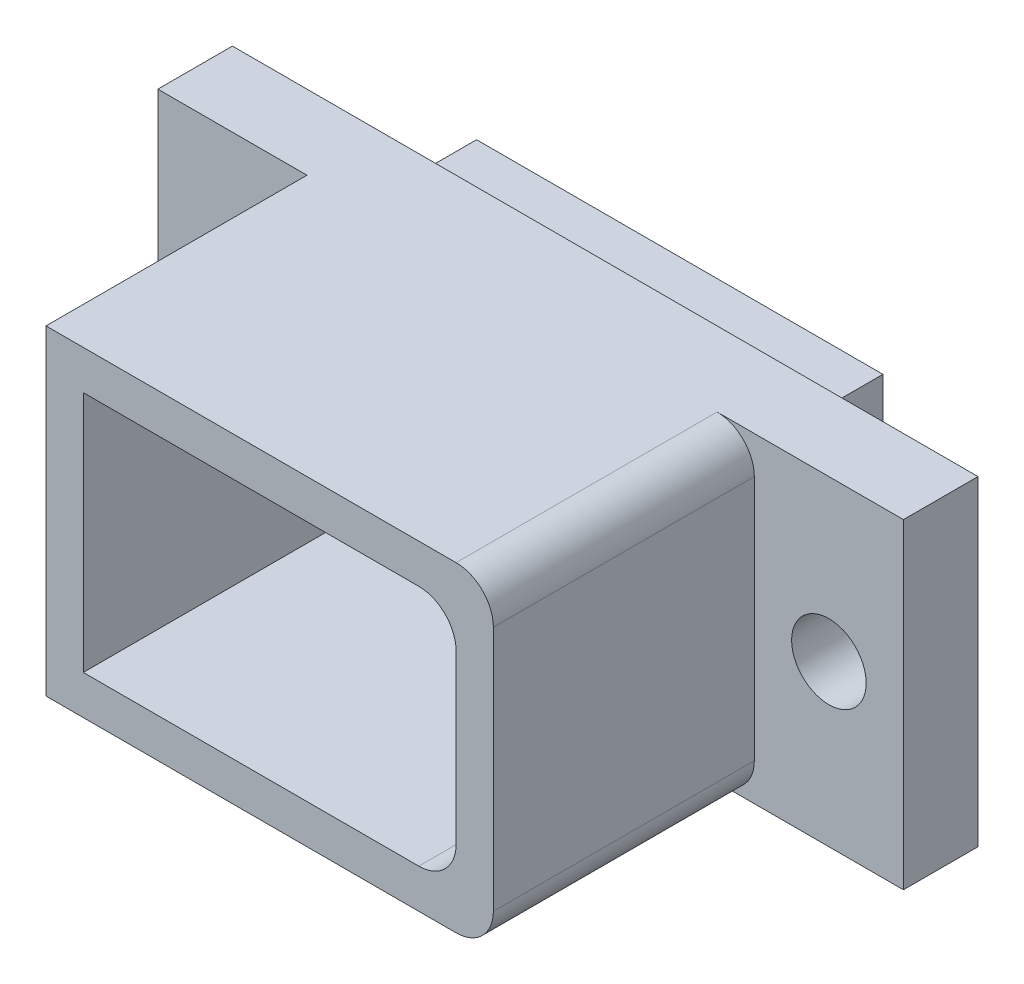
SolidWorks part; units mm, degrees
ref_plane "前视基准面" through (0, 0, 0) normal (0, 0, 1) x (1, 0, 0)
ref_plane "上视基准面" through (0, 0, 0) normal (0, 1, 0) x (1, 0, 0)
ref_plane "右视基准面" through (0, 0, 0) normal (1, 0, 0) x (0, 0, -1)
other "Configuration Table"
sketch "草图1" plane through (0, 0, 0) normal (0, 0, 1) x (1, 0, 0)
  line L0 (-3, 1.5) -> (0, 1.5) construction
  line L1 (-5.45, 3.4) -> (5.45, 3.4)
  line L2 (-5.45, 3.4) -> (-5.45, -3.4)
  line L3 (-5.45, -3.4) -> (5.45, -3.4)
  line L4 (5.45, 3.4) -> (5.45, -3.4)
  line L5 (-5.45, 3.4) -> (5.45, -3.4) construction
  line L6 (-5.45, -3.4) -> (5.45, 3.4) construction
  line L7 (-3, 1.5) -> (-3, -1.5) construction
  circle A0 centre (-3, 1.5) radius 0.5
  circle A1 centre (0, 1.5) radius 0.5
  circle A2 centre (3, 1.5) radius 0.5
  circle A3 centre (0, -1.5) radius 0.5
  circle A4 centre (3, -1.5) radius 0.5
  circle A5 centre (-3, -1.5) radius 0.5
  point P0 (0, 0)
  dimension "D10" = 1
  dimension "D1" = 6.8
  dimension "D2" = 10.9
  dimension "D3" = 2.45
  dimension "D4" = 1.9
  dimension "D5" = 90
  dimension "D6" = 3
  dimension "D7" = 3
  dimension "D8" = 3
  dimension "D9" = 2
extrude "凸台-拉伸1" add sketch "草图1" along normal blind 2
sketch "草图2" plane through (0, 0, 2) normal (0, 0, 1) x (1, 0, 0)
  line L0 (0, 0) -> (0, 9.4952) construction
  line L1 (-10, 4.3) -> (10, 4.3)
  line L2 (-10, 4.3) -> (-10, -4.3)
  line L3 (-10, -4.3) -> (10, -4.3)
  line L4 (10, 4.3) -> (10, -4.3)
  line L5 (-10, 4.3) -> (10, -4.3) construction
  line L6 (-10, -4.3) -> (10, 4.3) construction
  circle A0 centre (-8, 0) radius 1
  circle A1 centre (8, 0) radius 1
  circle A2 centre (3, 1.5) radius 0.5 construction
  circle A3 centre (3, -1.5) radius 0.5 construction
  circle A4 centre (0, -1.5) radius 0.5 construction
  circle A5 centre (0, 1.5) radius 0.5 construction
  circle A6 centre (-3, -1.5) radius 0.5 construction
  circle A7 centre (-3, 1.5) radius 0.5 construction
  circle A8 centre (3, 1.5) radius 0.5
  circle A9 centre (3, -1.5) radius 0.5
  circle A10 centre (0, -1.5) radius 0.5
  circle A11 centre (0, 1.5) radius 0.5
  circle A12 centre (-3, -1.5) radius 0.5
  circle A13 centre (-3, 1.5) radius 0.5
  point P0 (0, 0)
  dimension "D3" = 2
  dimension "D1" = 8.6
  dimension "D2" = 20
  dimension "D4" = 16
extrude "凸台-拉伸2" add sketch "草图2" along normal blind 2
sketch "草图3" plane through (0, 0, 4) normal (0, 0, 1) x (1, 0, 0)
  line L1 (-6, 4.3) -> (5, 4.3)
  line L2 (-6, 4.3) -> (-6, -4.3)
  line L3 (-6, -4.3) -> (5, -4.3)
  line L4 (6, 3.3) -> (6, -3.3)
  line L5 (-6, 4.3) -> (6, -4.3) construction
  line L6 (-6, -4.3) -> (6, 4.3) construction
  line L7 (-5, 3.25) -> (4, 3.25)
  line L8 (-5, 3.25) -> (-5, -3.25)
  line L9 (-5, -3.25) -> (4, -3.25)
  line L10 (5, 2.25) -> (5, -2.25)
  line L11 (-5, 3.25) -> (5, -3.25) construction
  line L12 (-5, -3.25) -> (5, 3.25) construction
  circle A0 centre (3, -1.5) radius 0.5 construction
  circle A1 centre (3, 1.5) radius 0.5 construction
  circle A2 centre (0, -1.5) radius 0.5 construction
  circle A3 centre (0, 1.5) radius 0.5 construction
  circle A4 centre (-3, -1.5) radius 0.5 construction
  circle A5 centre (-3, 1.5) radius 0.5 construction
  circle A6 centre (3, -1.5) radius 0.5
  circle A7 centre (3, 1.5) radius 0.5
  circle A8 centre (0, -1.5) radius 0.5
  circle A9 centre (0, 1.5) radius 0.5
  circle A10 centre (-3, -1.5) radius 0.5
  circle A11 centre (-3, 1.5) radius 0.5
  arc A12 (5, -4.3) -> (6, -3.3) centre (5, -3.3) ccw
  arc A13 (4, -3.25) -> (5, -2.25) centre (4, -2.25) ccw
  arc A14 (5, 4.3) -> (6, 3.3) centre (5, 3.3) cw
  arc A15 (4, 3.25) -> (5, 2.25) centre (4, 2.25) cw
  point P0 (0, 0)
  point P6 (0, 0)
  line M10 (10, 4.3) -> (-10, 4.3)
  line M12 (-10, -4.3) -> (10, -4.3)
  dimension "D5" = 1
  dimension "D1" = 12
  dimension "D2" = 8.6
  dimension "D3" = 10
  dimension "D4" = 6.5
extrude "凸台-拉伸3" add sketch "草图3" along normal blind 7 contours A14 L2 A12 L4 L7 A15 L10 A13 L9 L8 M10 M12
